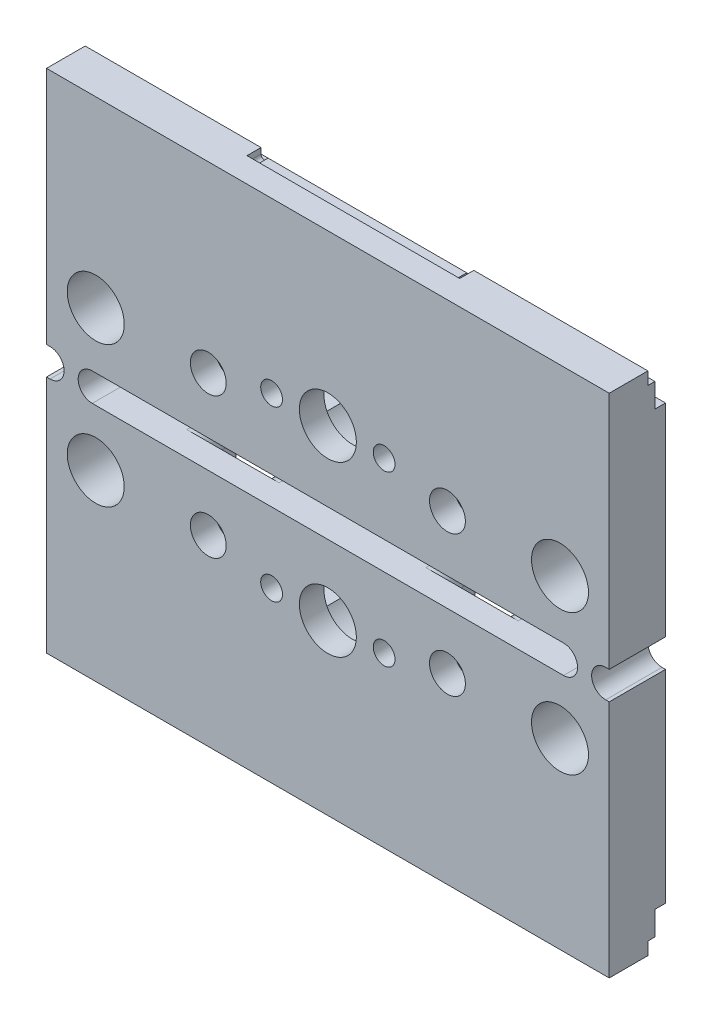
SolidWorks part; units mm, degrees
ref_plane "前视基准面" through (0, 0, 0) normal (0, 0, 1) x (1, 0, 0)
ref_plane "上视基准面" through (0, 0, 0) normal (0, 1, 0) x (1, 0, 0)
ref_plane "右视基准面" through (0, 0, 0) normal (1, 0, 0) x (0, 0, -1)
sketch "前视图草图" plane through (0, 0, 0) normal (0, 0, 1) x (1, 0, 0)
  line L0 (0, 0) -> (8.5179, 0) construction
  line L1 (0, 0) -> (0, 5.4227) construction
sketch "草图2" plane through (0, 0, 0) normal (0, 0, 1) x (1, 0, 0)
  line L0 (0, 0) -> (80, 0)
  line L1 (-200000, 0) -> (200008.5179, 0) construction
  line L2 (80, 0) -> (80, 34)
  line L3 (80, 34) -> (0, 34)
  line L4 (0, -200000) -> (0, 200005.4227) construction
  line L5 (0, 34) -> (0, 0)
  circle A0 centre (7, 8) radius 4.05
  circle A1 centre (40, 10) radius 4.05
  circle A2 centre (73, 8) radius 4.05
  dimension "D3" = 8
  dimension "D5" = 10
  dimension "D9" = 8.1
  dimension "D10" = 8.1
  dimension "D11" = 8.1
  dimension "D1" = 34
  dimension "D2" = 80
  dimension "D4" = 7
  dimension "D6" = 7
  dimension "D7" = 8
  dimension "D8" = 40
extrude "凸台-拉伸1" add sketch "草图2" along normal blind 8
sketch "草图3" plane through (0, 0, 8) normal (0, 0, 1) x (1, 0, 0)
  line L0 (16.088, 8) -> (31.4805, 8) construction
  line L1 (7, 8) -> (7, 16.8386) construction
  line L2 (73, 8) -> (73, 16.5917) construction
  line L4 (-200000, 0) -> (200008.5179, 0) construction
  circle A2 centre (23, 8) radius 2.55
  circle A3 centre (57, 8) radius 2.55
  dimension "D4" = 5.1
  dimension "D5" = 5.1
  dimension "D1" = 8
  dimension "D2" = 16
  dimension "D3" = 16
extrude "切除-拉伸1" cut sketch "草图3" against normal through all
sketch "草图4" plane through (80, 0, 0) normal (1, 0, 0) x (0, 0, -1)
  line L1 (0, -200000) -> (0, 200005.4227) construction
  line L2 (-1.5, 32.2) -> (-2.5, 32.2)
  line L3 (-2.5, 32.2) -> (-2.5, 34)
  line L4 (-8, 34) -> (0, 34) construction
  line L5 (-2.5, 34) -> (0, 34)
  line L6 (-1.5, 32.2) -> (-1.5, 28.8)
  line L7 (-1.5, 28.8) -> (0, 28.8)
  line L8 (0, 28.8) -> (0, 34)
  dimension "D1" = 3.4
  dimension "D2" = 2.5
  dimension "D3" = 1.5
  dimension "D4" = 1.8
extrude "切除-拉伸2" cut sketch "草图4" against normal through all
sketch "草图5" plane through (0, 0, 8) normal (0, 0, 1) x (1, 0, 0)
  line L0 (40, 10) -> (56.5376, 10) construction
  circle A0 centre (40, 10) radius 8 construction
  circle A1 centre (48, 10) radius 1.55
  circle A2 centre (32, 10) radius 1.55
  dimension "D1" = 3.1
  dimension "D2" = 3.1
  dimension "D3" = 16
extrude "切除-拉伸3" cut sketch "草图5" against normal through all
sketch "草图7" plane through (0, 0, 0) normal (0, 0, -1) x (-1, 0, 0)
  line L0 (-40, 12) -> (-40, -8.3696) construction
  line L1 (-23, 10) -> (-23, -2.3368) construction
  line L2 (200000, 0) -> (-200008.5179, 0) construction
  line L6 (-27.05, 10) -> (-27.05, 2.5)
  line L7 (-29.55, 0) -> (-16.45, 0)
  line L8 (-18.95, 2.5) -> (-18.95, 10)
  line L9 (-23, 8) -> (-23, 15.9045) construction
  line L13 (0, -200000) -> (0, 200005.4227) construction
  line L14 (-57, 8) -> (-57, 15.9045) construction
  line L15 (-57, 10) -> (-57, -2.3368) construction
  line L16 (-61.05, 2.5) -> (-61.05, 10)
  line L17 (-50.45, 0) -> (-63.55, 0)
  line L18 (-52.95, 10) -> (-52.95, 2.5)
  arc A1 (-18.95, 10) -> (-27.05, 10) centre (-23, 10) ccw
  arc A4 (-29.55, 0) -> (-27.05, 2.5) centre (-29.55, 2.5) ccw
  arc A5 (-18.95, 2.5) -> (-16.45, 0) centre (-16.45, 2.5) ccw
  arc A7 (-61.05, 2.5) -> (-63.55, 0) centre (-63.55, 2.5) cw
  arc A8 (-50.45, 0) -> (-52.95, 2.5) centre (-50.45, 2.5) cw
  arc A9 (-61.05, 10) -> (-52.95, 10) centre (-57, 10) cw
  dimension "D1" = 40
  dimension "D4" = 8.1
  dimension "D7" = 2.5
  dimension "D8" = 2.5
  dimension "D3" = 10
extrude "切除-拉伸4" cut sketch "草图7" against normal blind 4.5
sketch "草图8" plane through (0, 0, 0) normal (0, 0, -1) x (-1, 0, 0)
  line L0 (-40, 10) -> (-57.3165, 10) construction
  line L1 (-40, 20) -> (-40, 35.6562) construction
  line L2 (-30.5, 12.85) -> (-49.5, 12.85)
  line L3 (-49.5, 7.15) -> (-30.5, 7.15)
  line L4 (200000, 0) -> (-200008.5179, 0) construction
  arc A0 (-30.5, 7.15) -> (-30.5, 12.85) centre (-30.5, 10) ccw
  arc A1 (-49.5, 12.85) -> (-49.5, 7.15) centre (-49.5, 10) ccw
  dimension "D1" = 5.7
  dimension "D2" = 9.5
  dimension "D3" = 9.5
  dimension "D4" = 10
extrude "切除-拉伸5" cut sketch "草图8" against normal blind 4.5
sketch "草图20" plane through (0, 0, 0) normal (0, 0, -1) x (-1, 0, 0)
  circle A0 centre (-40, 10) radius 5.5
  dimension "D1" = 11
extrude "切除-拉伸12" cut sketch "草图20" against normal blind 4.5
sketch "草图19" plane through (0, 0, 2.5) normal (0, 0, -1) x (-1, 0, 0)
  line L0 (0, 34) -> (-80, 34) construction
  line L1 (-25, 34) -> (-55.2479, 34)
  line L2 (-25, 34) -> (-25, 33.2)
  line L3 (-26, 33.2) -> (-54.2479, 33.2)
  line L4 (-55.2479, 34) -> (-55.2479, 33.2)
  line L5 (0, -200000) -> (0, 200005.4227) construction
  line L7 (0, 32.2) -> (-80, 32.2) construction
  line L8 (-56.3335, 32.7) -> (-52.9089, 32.7) construction
  line L9 (-55.2479, 1028.5823) -> (-55.2479, 33.2) construction
  line L10 (-25, 1028.5823) -> (-25, 32.7) construction
  line L11 (-55.2479, 32.7) -> (-55.2479, -973.3) construction
  line L12 (-25, 32.7) -> (-25, -973.3) construction
  arc A3 (-55.2479, 33.2) -> (-54.2479, 33.2) centre (-54.7479, 33.2) ccw
  arc A6 (-26, 33.2) -> (-25, 33.2) centre (-25.5, 33.2) ccw
  dimension "D3" = 1
  dimension "D4" = 1
  dimension "D2" = 0.8
  dimension "D1" = 0.5
  dimension "D9" = 25
extrude "切除-拉伸11" cut sketch "草图19" against normal blind 2
sketch "草图22" plane through (0, 0, 8) normal (0, 0, 1) x (1, 0, 0)
  line L1 (0, -200000) -> (0, 200005.4227) construction
  line L2 (0.5, -4) -> (6.5, -4)
  line L4 (79.5, 0) -> (73.5, 0)
  line L5 (4.5, 1.9875) -> (4.5, -4.1402) construction
  line L6 (75.5, -11.5647) -> (75.5, -5.1636) construction
  line L7 (80, 0) -> (80, 34) construction
  line L8 (73.5, -4) -> (79.5, -4)
  line L9 (6.5, 0) -> (0.5, 0)
  line L10 (77.5, -2.9635) -> (77.5, -4.3032) construction
  line L11 (2.5, -8.393) -> (2.5, -15.1693) construction
  arc A0 (6.5, 0) -> (6.5, -4) centre (6.5, -2) ccw
  arc A1 (73.5, -4) -> (73.5, 0) centre (73.5, -2) ccw
  arc A2 (0.5, -4) -> (0.5, 0) centre (0.5, -2) ccw
  arc A3 (79.5, 0) -> (79.5, -4) centre (79.5, -2) ccw
  dimension "D1" = 4.5
  dimension "D2" = 4.5
  dimension "D3" = 4
  dimension "D4" = 2.5
  dimension "D5" = 2.5
extrude "凸台-拉伸2" add sketch "草图22" against normal blind 8
ref_plane "基准面1" through (0, -2, 0) normal (0, -1, 0) x (-1, 0, 0)
mirror "镜向2" about plane through (0, -2, 0) normal (0, -1, 0) of "切除-拉伸3", "凸台-拉伸1", "切除-拉伸1", "切除-拉伸2", "切除-拉伸4", "切除-拉伸5", "切除-拉伸12", "切除-拉伸11"
sketch "草图23" plane through (0, 0, 0) normal (0, 0, -1) x (-1, 0, 0)
  line L0 (-80, 0) -> (0, 0)
  line L1 (0, 0) -> (0, -4)
  line L2 (0, -4) -> (-80, -4)
  line L3 (-80, -4) -> (-80, 0)
sketch "草图24" plane through (0, 0, 8) normal (0, 0, 1) x (1, 0, 0)
  line L0 (80, -4) -> (80, 0)
  line L1 (80, 0) -> (0, 0)
  line L2 (0, 0) -> (0, -4)
  line L3 (0, -4) -> (80, -4)
